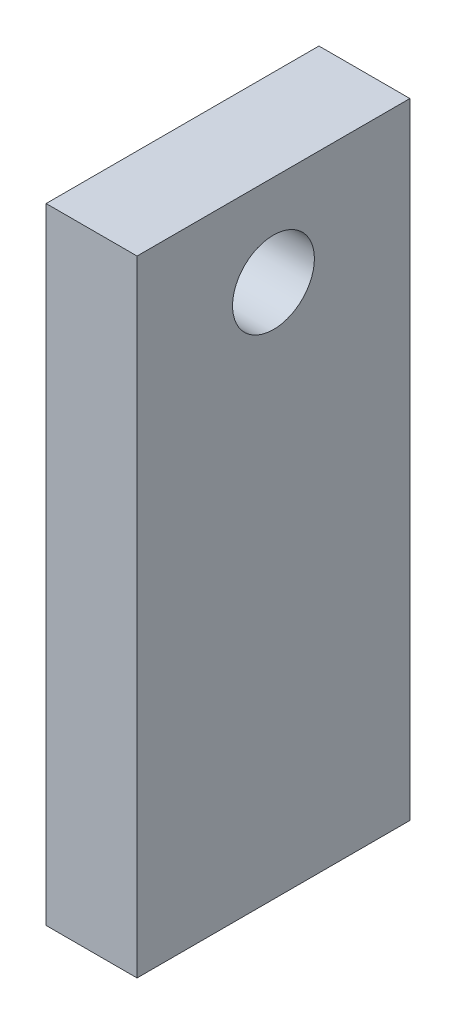
SolidWorks part; units mm, degrees
ref_plane "Front Plane" through (0, 0, 0) normal (0, 0, 1) x (1, 0, 0)
ref_plane "Top Plane" through (0, 0, 0) normal (0, 1, 0) x (1, 0, 0)
ref_plane "Right Plane" through (0, 0, 0) normal (1, 0, 0) x (0, 0, -1)
sketch "Sketch1" plane through (0, 0, 0) normal (1, 0, 0) x (0, 0, -1)
  line L1 (150, -343.75) -> (-150, -343.75)
  line L2 (150, -343.75) -> (150, 343.75)
  line L3 (150, 343.75) -> (-150, 343.75)
  line L4 (-150, -343.75) -> (-150, 343.75)
  line L5 (150, -343.75) -> (-150, 343.75) construction
  line L6 (150, 343.75) -> (-150, -343.75) construction
  circle A0 centre (0, 243.75) radius 45
  point P0 (0, 0)
  dimension "D1" = 587.5
  dimension "D2" = 90
  dimension "D3" = 100
  dimension "D4" = 150
  dimension "D5" = 150
extrude "Boss-Extrude1" add sketch "Sketch1" along normal blind 100
